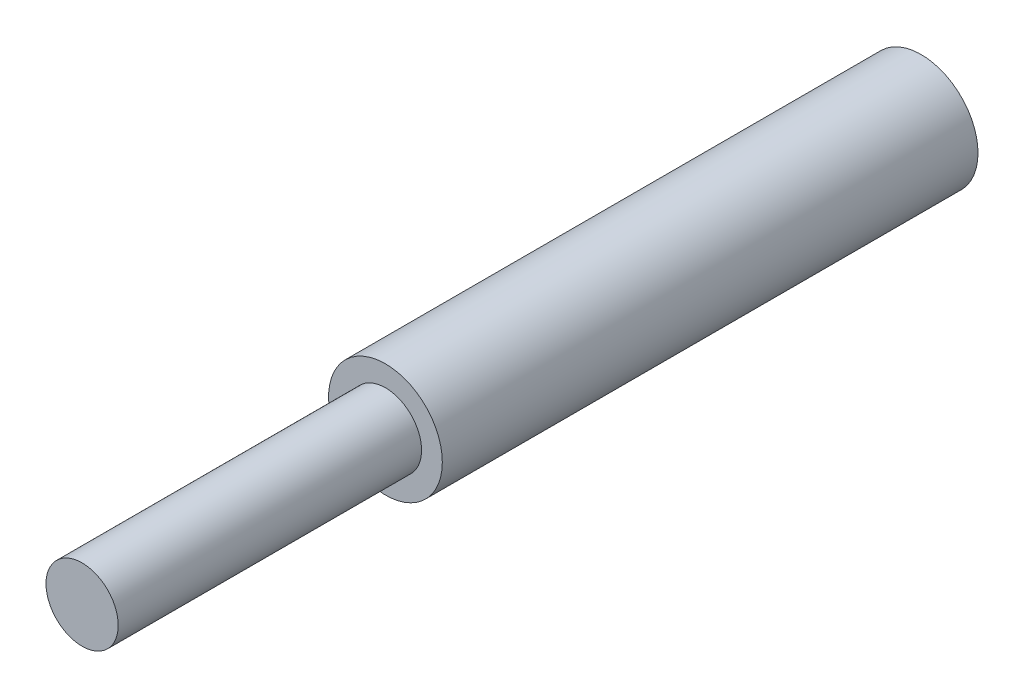
SolidWorks part; units mm, degrees
ref_plane "Front Plane" through (0, 0, 0) normal (0, 0, 1) x (1, 0, 0)
ref_plane "Top Plane" through (0, 0, 0) normal (0, 1, 0) x (1, 0, 0)
ref_plane "Right Plane" through (0, 0, 0) normal (1, 0, 0) x (0, 0, -1)
sketch "Sketch1" plane through (0, 0, 0) normal (0, 0, 1) x (1, 0, 0)
  circle A0 centre (-11.8336, 2.7372) radius 3.937
  dimension "D1" = 7.874
extrude "Boss-Extrude1" add sketch "Sketch1" along normal blind 37.084
sketch "Sketch3" plane through (0, 0, 37.084) normal (0, 0, 1) x (1, 0, 0)
  circle A1 centre (-11.8336, 2.7372) radius 2.5
  dimension "D1" = 5
extrude "Boss-Extrude2" add sketch "Sketch3" along normal blind 21
